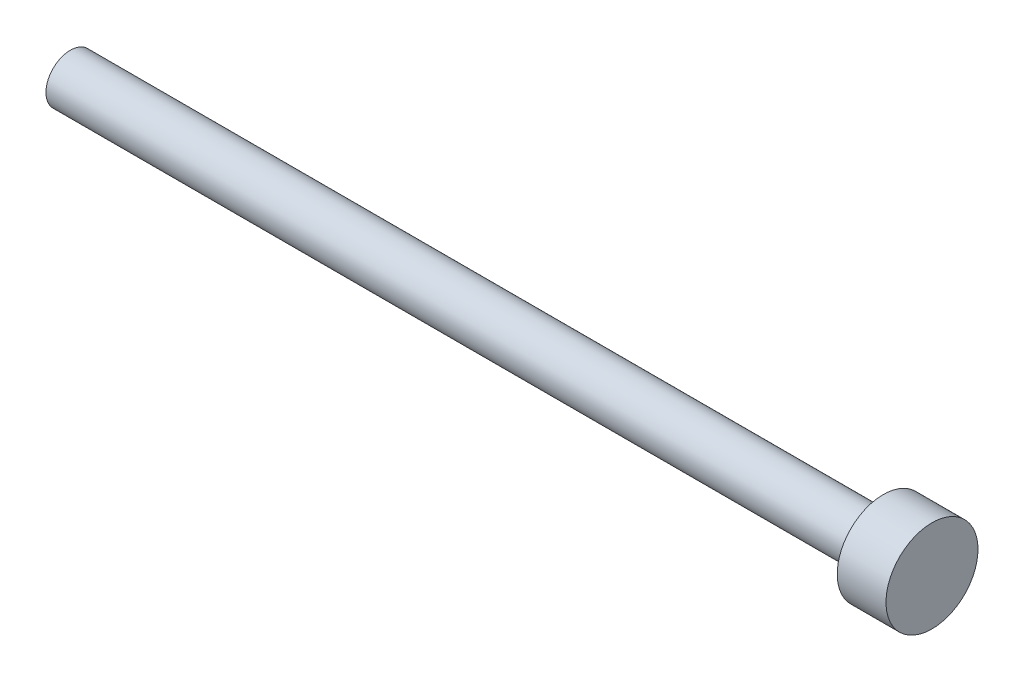
SolidWorks part; units mm, degrees
ref_plane "前视基准面" through (0, 0, 0) normal (0, 0, 1) x (1, 0, 0)
ref_plane "上视基准面" through (0, 0, 0) normal (0, 1, 0) x (1, 0, 0)
ref_plane "右视基准面" through (0, 0, 0) normal (1, 0, 0) x (0, 0, -1)
sketch "草图1" plane through (0, 0, 0) normal (1, 0, 0) x (0, 0, -1)
  circle A0 centre (0, 0) radius 1.5
extrude "凸台-拉伸2" add sketch "草图1" along normal blind 50
sketch "草图2" plane through (50, 0, 0) normal (1, 0, 0) x (0, 0, -1)
  circle A0 centre (0, 0) radius 2.83
extrude "凸台-拉伸3" add sketch "草图2" along normal blind 3
